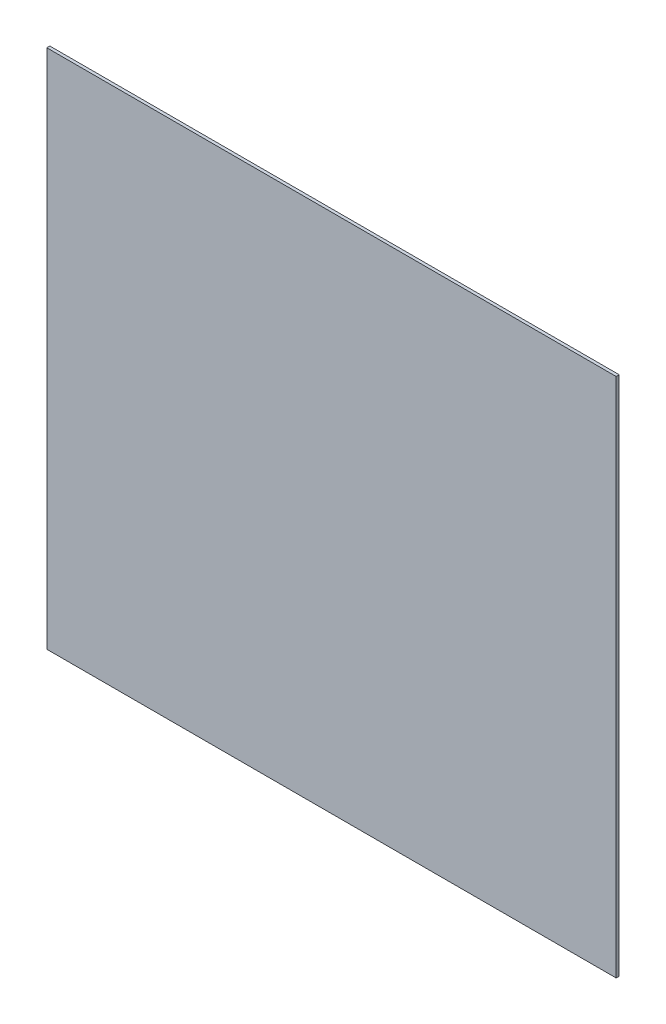
SolidWorks part; units mm, degrees
material "PC High Viscosity"
ref_plane "Front Plane" through (0, 0, 0) normal (0, 0, 1) x (1, 0, 0)
ref_plane "Top Plane" through (0, 0, 0) normal (0, 1, 0) x (1, 0, 0)
ref_plane "Right Plane" through (0, 0, 0) normal (1, 0, 0) x (0, 0, -1)
sketch "Shelf opening" plane through (0, 0, 0) normal (0, 0, 1) x (1, 0, 0)
  line L1 (-273.05, 0) -> (273.05, 0)
  line L2 (-273.05, 0) -> (-273.05, 520.7)
  line L3 (-273.05, 520.7) -> (273.05, 520.7)
  line L4 (273.05, 0) -> (273.05, 520.7)
  dimension "D1" = 520.7
  dimension "D2" = 546.1
sketch "Sketch2" plane through (0, 0, 0) normal (0, 0, 1) x (1, 0, 0)
  line L0 (-273.05, 0) -> (273.05, 0) construction
  line L1 (-298.45, 0) -> (298.45, 0)
  line L2 (-298.45, 0) -> (-298.45, 546.1)
  line L3 (-298.45, 546.1) -> (298.45, 546.1)
  line L4 (298.45, 0) -> (298.45, 546.1)
  line L5 (273.05, 0) -> (273.05, 520.7) construction
  line L6 (-273.05, 0) -> (-273.05, 520.7) construction
  line L7 (-273.05, 520.7) -> (273.05, 520.7) construction
  dimension "D1" = 25.4
  dimension "D2" = 25.4
  dimension "D3" = 25.4
extrude "Boss-Extrude1" add sketch "Sketch2" along normal blind 3.175
equation "\"D2@Sketch2\"=\"D1@Sketch2\""
